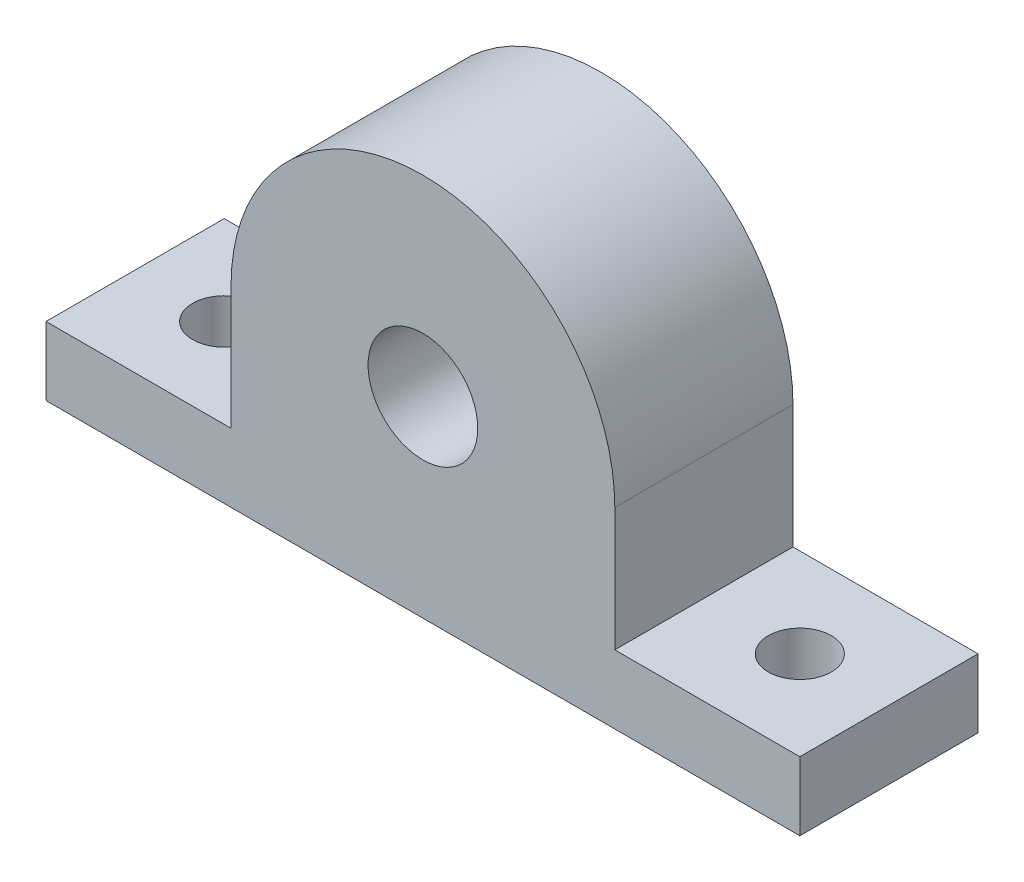
SolidWorks part; units mm, degrees
ref_plane "Front Plane" through (0, 0, 0) normal (0, 0, 1) x (1, 0, 0)
ref_plane "Top Plane" through (0, 0, 0) normal (0, 1, 0) x (1, 0, 0)
ref_plane "Right Plane" through (0, 0, 0) normal (1, 0, 0) x (0, 0, -1)
sketch "Sketch1" plane through (0, 0, 0) normal (0, 1, 0) x (1, 0, 0)
  line L1 (0, 0) -> (55, 0)
  line L2 (0, 0) -> (0, 13)
  line L3 (0, 13) -> (55, 13)
  line L4 (55, 0) -> (55, 13)
  dimension "D1" = 55
  dimension "D2" = 13
extrude "Boss-Extrude1" add sketch "Sketch1" along normal blind 5
sketch "Sketch2" plane through (0, 0, 0) normal (0, 0, 1) x (1, 0, 0)
  line L0 (55, 5) -> (55, 0) construction
  line L1 (0, 0) -> (55, 0) construction
  line L2 (13.5, 14) -> (13.5, 0)
  line L3 (13.5, 0) -> (41.5, 0)
  line L4 (41.5, 0) -> (41.5, 14)
  arc A0 (41.5, 14) -> (13.5, 14) centre (27.5, 14) ccw
  circle A1 centre (27.5, 14) radius 4
  dimension "D1" = 28
  dimension "D4" = 8
  dimension "D2" = 27.5
  dimension "D3" = 14
extrude "Boss-Extrude2" add sketch "Sketch2" against normal blind 13
sketch "Sketch3" plane through (0, 5, 0) normal (0, 1, 0) x (1, 0, 0)
  line L0 (41.5, 0) -> (55, 0) construction
  line L1 (0, 13) -> (0, 0) construction
  circle A0 centre (48.5, 6.5) radius 2.3
  circle A1 centre (6.5, 6.5) radius 2.3
  dimension "D1" = 4.6
  dimension "D3" = 4.6
  dimension "D2" = 6.5
  dimension "D4" = 42
  dimension "D5" = 6.5
extrude "Cut-Extrude1" cut sketch "Sketch3" against normal up to next
